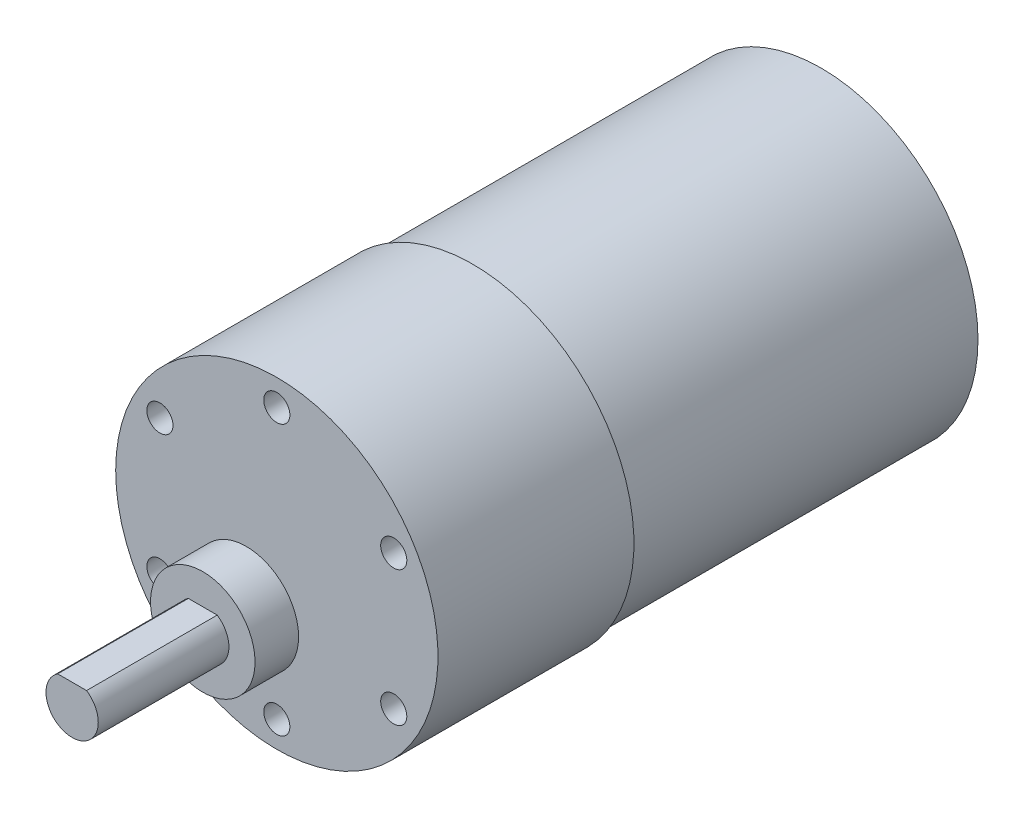
SolidWorks part; units mm, degrees
material "合金钢"
ref_plane "前视基准面" through (0, 0, 0) normal (0, 0, 1) x (1, 0, 0)
ref_plane "上视基准面" through (0, 0, 0) normal (0, 1, 0) x (1, 0, 0)
ref_plane "右视基准面" through (0, 0, 0) normal (1, 0, 0) x (0, 0, -1)
sketch "草图1" plane through (0, 0, 0) normal (0, 0, 1) x (1, 0, 0)
  circle A0 centre (0, 0) radius 18
  dimension "D1" = 36
extrude "凸台-拉伸1" add sketch "草图1" against normal blind 40
sketch "草图2" plane through (0, 0, 0) normal (0, 0, 1) x (1, 0, 0)
  circle A0 centre (0, 0) radius 18.5
  dimension "D1" = 37
extrude "凸台-拉伸2" add sketch "草图2" along normal blind 22.5
sketch "草图3" plane through (0, 0, 22.5) normal (0, 0, 1) x (1, 0, 0)
  line L0 (-3.5, -6.0622) -> (0, 0) construction
  line L1 (0, 0) -> (0, 50000) construction
  circle A0 centre (-3.5, -6.0622) radius 6
  dimension "D1" = 7
  dimension "D2" = 12
  dimension "D3" = 30
extrude "凸台-拉伸3" add sketch "草图3" along normal blind 5
sketch "草图4" plane through (0, 0, 22.5) normal (0, 0, 1) x (1, 0, 0)
  line L0 (-1.8417, -3.5622) -> (-5.1583, -3.5622)
  circle A0 centre (-3.5, -6.0622) radius 3 construction
  arc A1 (-5.1583, -3.5622) -> (-1.8417, -3.5622) centre (-3.5, -6.0622) ccw
  point P2 (-3.5, -6.0622)
  dimension "D1" = 6
  dimension "D2" = 2.5
extrude "凸台-拉伸4" add sketch "草图4" along normal blind 20
sketch "草图5" plane through (0, 0, 22.5) normal (0, 0, 1) x (1, 0, 0)
  line L0 (0, 0) -> (0, 15.5) construction
  circle A0 centre (0, 15.5) radius 1.5
  dimension "D2" = 3
  dimension "D1" = 15.5
extrude "切除-拉伸1" cut sketch "草图5" against normal blind 5
sketch "草图6" plane through (0, 0, 0) normal (0, 1, 0) x (1, 0, 0)
  line L0 (0, 0) -> (0, -50000) construction
pattern_circular "阵列(圆周)1" count 6 over 360 about axis through (0, 0, 0) along (0, 0, 1) of "切除-拉伸1"
